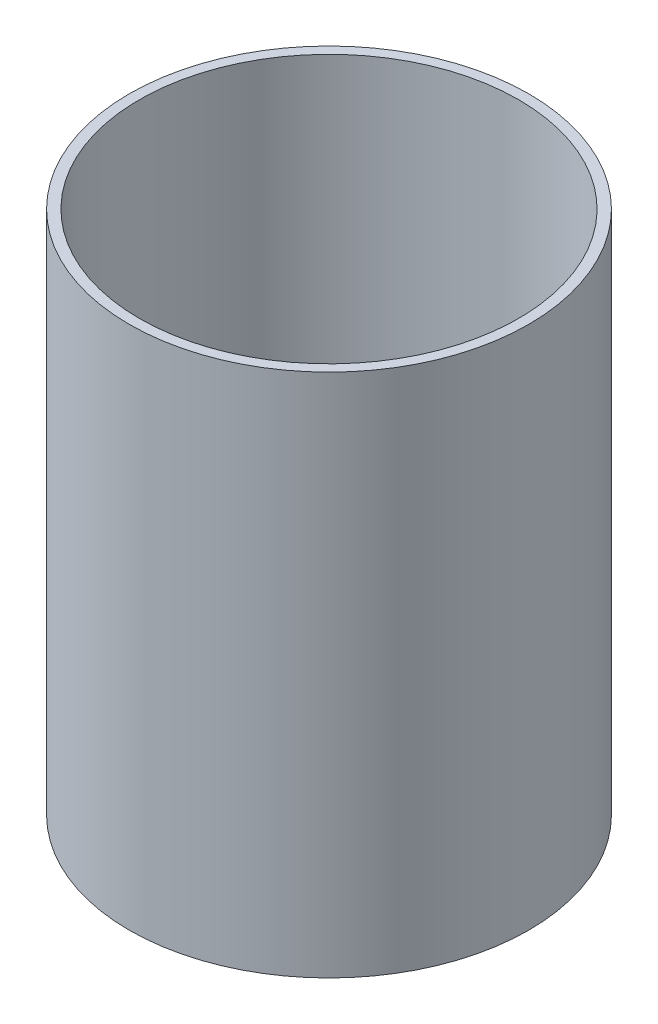
SolidWorks part; units mm, degrees
material "A-Glass Fiber"
ref_plane "Front" through (0, 0, 0) normal (0, 0, 1) x (1, 0, 0)
ref_plane "Top" through (0, 0, 0) normal (0, 1, 0) x (1, 0, 0)
ref_plane "Right" through (0, 0, 0) normal (1, 0, 0) x (0, 0, -1)
sketch "Sketch2" plane through (0, 0, 0) normal (0, 1, 0) x (1, 0, 0)
  circle A0 centre (0, 0) radius 59
  circle A1 centre (0, 0) radius 56
  dimension "D1" = 118
  dimension "D2" = 3
extrude "Boss-Extrude2" add sketch "Sketch2" along normal blind 155
